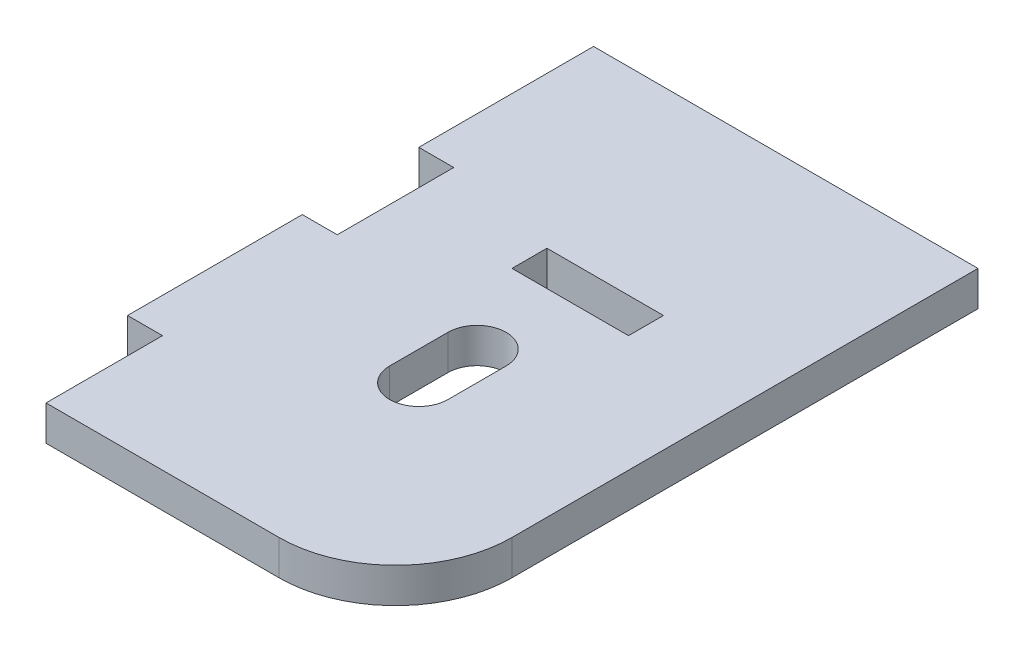
SolidWorks part; units mm, degrees
material "ABS PC"
ref_plane "Front Plane" through (0, 0, 0) normal (0, 0, 1) x (1, 0, 0)
ref_plane "Top Plane" through (0, 0, 0) normal (0, 1, 0) x (1, 0, 0)
ref_plane "Right Plane" through (0, 0, 0) normal (1, 0, 0) x (0, 0, -1)
sketch "Sketch1" plane through (0, 0, 0) normal (0, 1, 0) x (1, 0, 0)
  line L0 (-33, 0) -> (-33, -15)
  line L1 (-33, -15) -> (-30, -15)
  line L2 (-30, -15) -> (-30, -25)
  line L3 (-30, -25) -> (-33, -25)
  line L4 (-33, -25) -> (-33, -40)
  line L5 (-33, -40) -> (-30, -40)
  line L6 (-30, -40) -> (-30, -50)
  line L7 (-30, -50) -> (0, -50)
  line L8 (0, -50) -> (0, 0)
  line L9 (0, 0) -> (-33, 0)
  line L11 (-20, -17) -> (-10, -17)
  line L12 (-20, -17) -> (-20, -20)
  line L13 (-20, -20) -> (-10, -20)
  line L14 (-10, -17) -> (-10, -20)
  dimension "D1" = 15
  dimension "D2" = 10
  dimension "D3" = 3
  dimension "D4" = 30
  dimension "D5" = 10
  dimension "D6" = 10
  dimension "D7" = 30
extrude "Boss-Extrude1" add sketch "Sketch1" along normal blind 3
sketch "Sketch2" plane through (0, 3, 0) normal (0, 1, 0) x (1, 0, 0)
  line L0 (-15.5, -32.5) -> (-15.5, -27.5) construction
  line L1 (-18, -32.5) -> (-18, -27.5)
  line L2 (-13, -32.5) -> (-13, -27.5)
  line L3 (-15.5, -32.5) -> (-15.5, -50) construction
  line L4 (-30, -50) -> (0, -50) construction
  line L5 (0, -50) -> (0, 0) construction
  arc A0 (-18, -32.5) -> (-13, -32.5) centre (-15.5, -32.5) ccw
  arc A1 (-13, -27.5) -> (-18, -27.5) centre (-15.5, -27.5) ccw
  point P2 (-15.5, -30)
  dimension "D1" = 2.5
  dimension "D2" = 5
  dimension "D3" = 20
  dimension "D4" = 15.5
extrude "Cut-Extrude1" cut sketch "Sketch2" against normal through all
fillet "Fillet1" radius 10 1 edges at (0, 1.5, 50)
